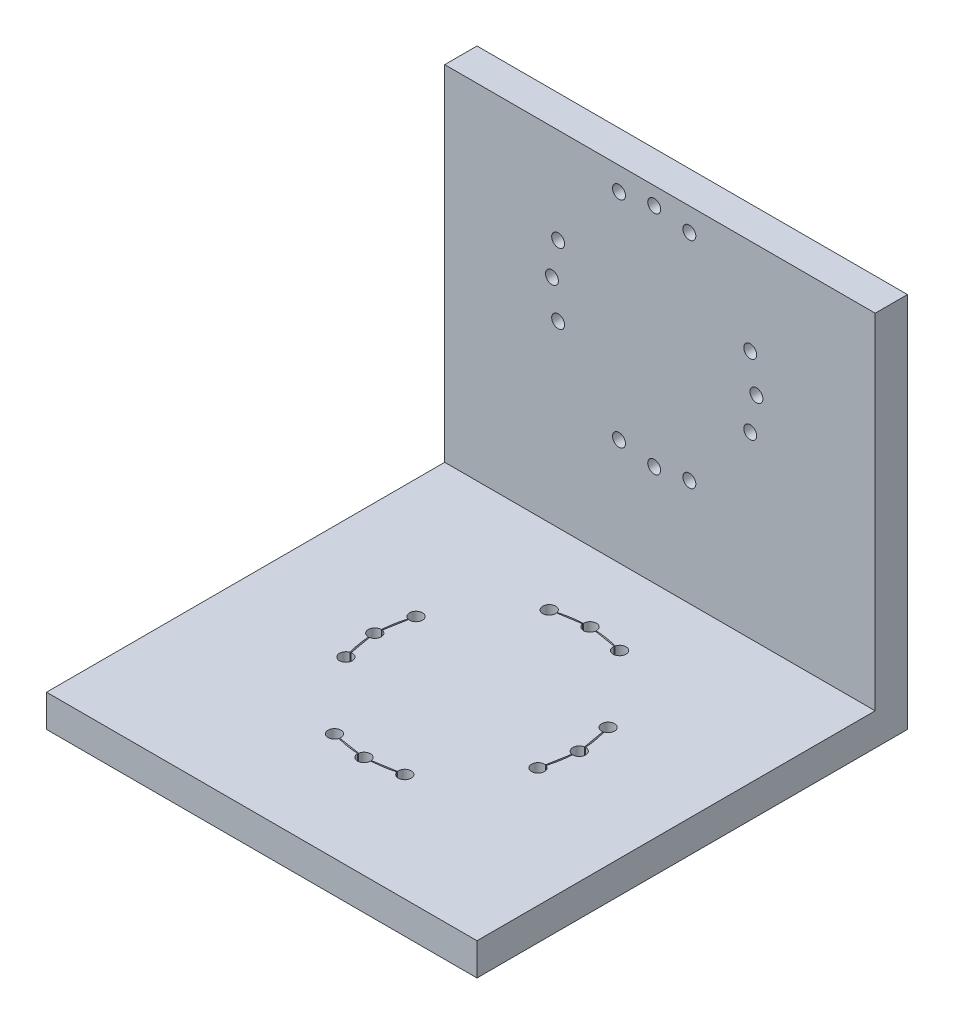
SolidWorks part; units mm, degrees
ref_plane "Plan de face" through (0, 0, 0) normal (0, 0, 1) x (1, 0, 0)
ref_plane "Plan de dessus" through (0, 0, 0) normal (0, 1, 0) x (1, 0, 0)
ref_plane "Plan de droite" through (0, 0, 0) normal (1, 0, 0) x (0, 0, -1)
sketch "Esquisse1" plane through (0, 0, 0) normal (0, 1, 0) x (1, 0, 0)
  line L0 (-21.6009, 17.4725) -> (18.3991, 17.4725)
  line L1 (-21.6009, 17.4725) -> (-21.6009, -22.5275)
  line L2 (18.3991, 17.4725) -> (18.3991, -22.5275)
  line L3 (-21.6009, -22.5275) -> (18.3991, -22.5275)
  line L4 (-1.6009, 17.4725) -> (-1.6009, -22.5275)
  line L5 (-1.6009, -22.5275) -> (-1.6009, -2.5275)
  line L6 (10.3991, -2.5275) -> (7.8991, -2.5275)
  line L7 (-13.6009, -2.5275) -> (-11.1009, -2.5275)
  line L8 (-1.6009, 7.9725) -> (1.6677, 7.4508)
  line L9 (-1.6009, 7.9725) -> (-4.8695, 7.4508)
  line L10 (-1.6009, -13.0275) -> (1.6677, -12.5058)
  line L11 (-1.6009, -13.0275) -> (-4.8695, -12.5058)
  line L12 (-11.1009, -2.5275) -> (-10.5243, 0.7319)
  line L13 (-11.1009, -2.5275) -> (-10.5243, -5.7869)
  line L14 (7.8991, -2.5275) -> (7.3224, 0.7319)
  line L15 (7.8991, -2.5275) -> (7.3224, -5.7869)
  circle A0 centre (-1.6009, -2.5275) radius 12
  circle A1 centre (-1.6009, -2.5275) radius 10.5
  circle A2 centre (7.8991, -2.5275) radius 0.6
  circle A3 centre (-11.1009, -2.5275) radius 0.6
  circle A4 centre (-1.6009, 7.9725) radius 0.6
  circle A5 centre (-1.6009, -13.0275) radius 0.6
  circle A6 centre (1.6677, 7.4508) radius 0.6
  circle A7 centre (-4.8695, 7.4508) radius 0.6
  circle A8 centre (-4.8695, -12.5058) radius 0.6
  circle A9 centre (1.6677, -12.5058) radius 0.6
  circle A10 centre (-1.6009, -2.5275) radius 9.5
  circle A11 centre (-10.5243, 0.7319) radius 0.6
  circle A12 centre (-10.5243, -5.7869) radius 0.6
  circle A13 centre (7.3224, 0.7319) radius 0.6
  circle A14 centre (7.3224, -5.7869) radius 0.6
  dimension "D1" = 40
  dimension "D2" = 40
extrude "Boss.-Extru.1" add sketch "Esquisse1" along normal blind 3 contours A0 L4 L0 L1 L3 | A8 A1 L7 A0 L4 A5 | A7 A1 A4 L4 A0 L7 | A12 A10 A3 L7 A1 A8 L11 A5 L5 | A11 A10 L4 A4 L9 A7 A1 L7 A3 | A12 A10 L4 A11 L12 A3 L13 | A14 L15 A2 L14 A13 A10 L4 | A14 A10 L5 A5 L10 A9 A1 L6 A2 | A13 A10 A2 L6 A1 A6 L8 A4 L4 | A6 A1 L6 A0 L4 A4 | A9 A1 A5 L4 A0 L6 | A0 L4 L3 L2 L0
sketch "Esquisse2" plane through (0, 3, 0) normal (0, 1, 0) x (1, 0, 0)
  line L0 (-1.6009, 17.4725) -> (-1.6009, 14.4725)
  line L1 (-21.6009, 17.4725) -> (18.3991, 17.4725) construction
  line L2 (-1.6009, 17.4725) -> (-21.6009, 17.4725)
  line L3 (-21.6009, 17.4725) -> (-21.6009, 14.4725)
  line L4 (-21.6009, 17.4725) -> (-21.6009, -22.5275) construction
  line L5 (-21.6009, 14.4725) -> (-1.6009, 14.4725)
  line L6 (-1.6009, 17.4725) -> (18.3991, 17.4725)
  line L7 (18.3991, 17.4725) -> (18.3991, 14.4725)
  line L8 (18.3991, 17.4725) -> (18.3991, -22.5275) construction
  line L9 (18.3991, 14.4725) -> (-1.6009, 14.4725)
  line L10 (-1.6009, 17.4725) -> (18.3991, 17.4725)
  line M33 (18.3991, -22.5275) -> (18.3991, 17.4725)
  line M34 (18.3991, 17.4725) -> (-21.6009, 17.4725)
  line M35 (-21.6009, 17.4725) -> (-21.6009, -22.5275)
extrude "Boss.-Extru.2" add sketch "Esquisse2" along normal blind 32 contours L5 L0 M35 M34 | L9 L0 M33 M34
sketch "Esquisse3" plane through (0, 0, -14.4725) normal (0, 0, 1) x (1, 0, 0)
  circle A0 centre (7.3628, 22.8773) radius 0.6
  circle A1 centre (-11.6372, 22.8773) radius 0.6
  circle A2 centre (-2.1372, 33.3773) radius 0.6
  circle A3 centre (-2.1372, 12.3773) radius 0.6
  circle A4 centre (1.1314, 32.8556) radius 0.6
  circle A5 centre (-5.4058, 32.8556) radius 0.6
  circle A6 centre (-5.4058, 12.899) radius 0.6
  circle A7 centre (1.1314, 12.899) radius 0.6
  circle A8 centre (-11.0606, 26.1367) radius 0.6
  circle A9 centre (-11.0606, 19.6179) radius 0.6
  circle A10 centre (6.7861, 26.1367) radius 0.6
  circle A11 centre (6.7861, 19.6179) radius 0.6
  point P24 (0, 0)
extrude "Enlèv. mat.-Extru.1" cut sketch "Esquisse3" against normal blind 32
